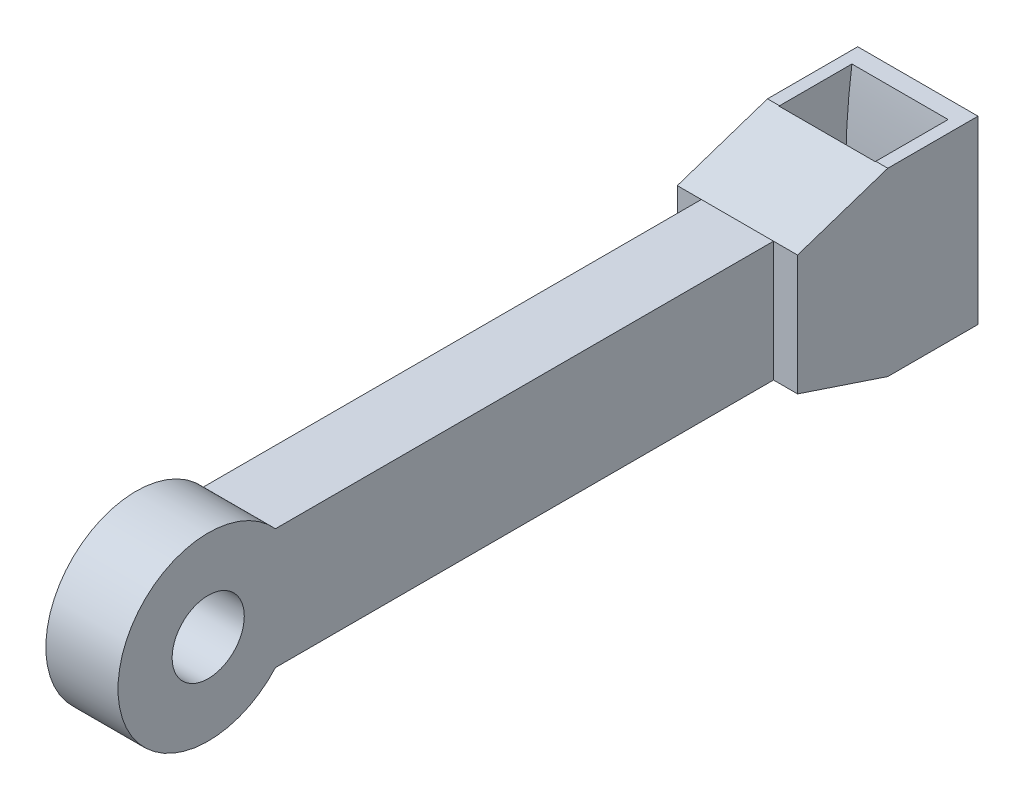
SolidWorks part; units mm, degrees
ref_plane "Front Plane" through (0, 0, 0) normal (0, 0, 1) x (1, 0, 0)
ref_plane "Top Plane" through (0, 0, 0) normal (0, 1, 0) x (1, 0, 0)
ref_plane "Right Plane" through (0, 0, 0) normal (1, 0, 0) x (0, 0, -1)
sketch "Sketch1" plane through (0, 0, 0) normal (0, 0, 1) x (1, 0, 0)
  line L1 (0, 0) -> (10, 0)
  line L2 (0, 0) -> (0, -15)
  line L3 (0, -15) -> (10, -15)
  line L4 (10, 0) -> (10, -15)
  dimension "D1" = 10
  dimension "D2" = 15
extrude "Boss-Extrude1" add sketch "Sketch1" along normal blind 15
sketch "Sketch2" plane through (10, 0, 0) normal (1, 0, 0) x (0, 0, -1)
  line L0 (-7.5, 0) -> (-7.5, -15) construction
  line L1 (-15, 0) -> (0, 0) construction
  line L2 (-15, -15) -> (0, -15) construction
  line L3 (-7.5, 0) -> (-15, -2.5)
  line L4 (-15, -15) -> (-15, 0) construction
  line L5 (-7.5, -15) -> (-15, -12.5)
  line L6 (-15, -2.5) -> (-15, 0)
  line L7 (-15, 0) -> (-7.5, 0)
  line L8 (-15, -12.5) -> (-15, -15)
  line L9 (-15, -15) -> (-7.5, -15)
  dimension "D1" = 2.5
  dimension "D2" = 2.5
extrude "Cut-Extrude1" cut sketch "Sketch2" against normal blind 30
sketch "Sketch3" plane through (0, 0, 15) normal (0, 0, 1) x (1, 0, 0)
  line L1 (0, -2.5) -> (10, -2.5) construction
  line L2 (10, -12.5) -> (10, -2.5) construction
  circle A0 centre (5, -7.5) radius 2.5
  dimension "D1" = 5
  dimension "D3" = 5
  dimension "D2" = 5
sketch "Sketch12" plane through (10, 0, 0) normal (1, 0, 0) x (0, 0, -1)
  line L0 (-5, -7.5) -> (-8, -7.5) construction
  line L1 (-8, -7.5) -> (-2.7948, 1.0385) construction
  line L3 (0, -15) -> (0, 0) construction
  line L5 (-7.5, -15) -> (0, -15) construction
  line L6 (-15, -5) -> (-15, -10) construction
  arc A0 (10.1335, -46.4324) -> (10.1335, 31.4324) centre (52.6456, -7.5) cw construction
  arc A1 (7.9211, 33.4586) -> (7.9211, -48.4586) centre (52.6456, -7.5) ccw
  arc A2 (12.3459, 29.4063) -> (12.3459, -44.4063) centre (52.6456, -7.5) ccw
  arc A3 (12.3459, 29.4063) -> (7.9211, 33.4586) centre (10.1335, 31.4324) ccw
  arc A4 (7.9211, -48.4586) -> (12.3459, -44.4063) centre (10.1335, -46.4324) ccw
  point P3 (-5, -7.5)
  point P15 (-8, -7.5)
  dimension "D1" = 10
  dimension "D2" = 7.5
extrude "Cut-Extrude3" cut sketch "Sketch12" against normal blind 4 and the other way blind 4 from offset 5 offset against normal yes
ref_plane "Plane3" through (0, 0, 8) normal (0, 0, 1) x (1, 0, 0)
sketch "Sketch13" plane through (0, 0, 15) normal (0, 0, 1) x (1, 0, 0)
  line L1 (0, -2.5) -> (10, -2.5)
  line L2 (0, -2.5) -> (0, -12.5)
  line L3 (0, -12.5) -> (10, -12.5)
  line L4 (10, -2.5) -> (10, -12.5)
extrude "Boss-Extrude2" add sketch "Sketch13" along normal blind 52
sketch "Sketch14" plane through (0, 0, 0) normal (-1, 0, 0) x (0, 0, 1)
  line L0 (67, -7.5) -> (62, -7.5) construction
  line L1 (67, -2.5) -> (67, -12.5) construction
  circle A0 centre (62, -7.5) radius 5
  circle A1 centre (62, -7.5) radius 7.5
  dimension "D1" = 15
  dimension "D2" = 10
extrude "Boss-Extrude3" add sketch "Sketch14" against normal blind 10
sketch "Sketch16" plane through (0, 0, 0) normal (-1, 0, 0) x (0, 0, 1)
  circle A2 centre (62, -7.5) radius 3
  dimension "D1" = 6
extrude "Cut-Extrude4" cut sketch "Sketch16" against normal blind 10 contours A2
sketch "Sketch10" plane through (10, 0, 0) normal (1, 0, 0) x (0, 0, -1)
  line L0 (0, 5.5) -> (0, -5.5) construction
  line L1 (-7.5, -15) -> (0, -15) construction
  circle A0 centre (-3, -7.5) radius 2
  dimension "D1" = 4
  dimension "D2" = 3
  dimension "D3" = 7.5
sketch "Sketch17" plane through (0, -2.5, 0) normal (0, 1, 0) x (1, 0, 0)
  line L1 (0, -15) -> (2, -15)
  line L2 (0, -15) -> (0, -71.7514)
  line L3 (0, -71.7514) -> (2, -71.7514)
  line L4 (2, -15) -> (2, -71.7514)
  line L6 (10, -15) -> (8, -15)
  line L7 (10, -15) -> (10, -75.929)
  line L8 (10, -75.929) -> (8, -75.929)
  line L9 (8, -15) -> (8, -75.929)
extrude "Cut-Extrude5" cut sketch "Sketch17" against normal blind 20 and the other way blind 10
